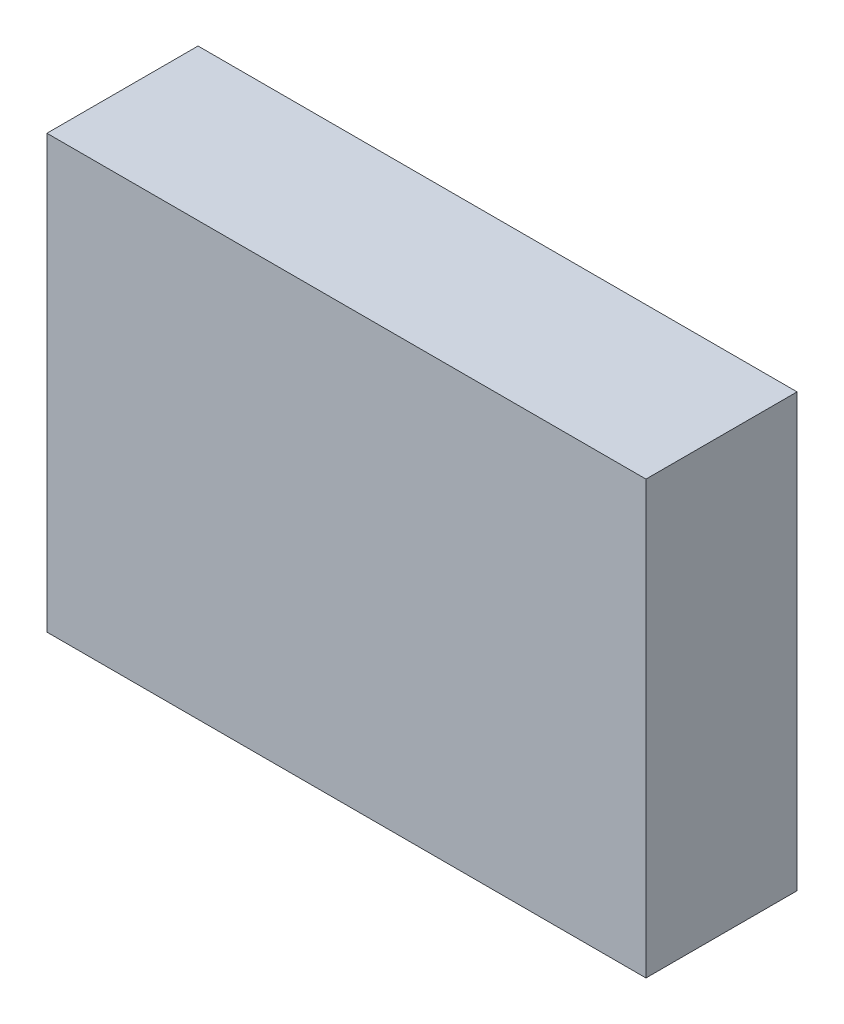
SolidWorks part; units mm, degrees
ref_plane "Front" through (0, 0, 0) normal (0, 0, 1) x (1, 0, 0)
ref_plane "Top" through (0, 0, 0) normal (0, 1, 0) x (1, 0, 0)
ref_plane "Right" through (0, 0, 0) normal (1, 0, 0) x (0, 0, -1)
sketch "Esboço1" plane through (0, 0, 0) normal (0, 0, 1) x (1, 0, 0)
  line L1 (-19.8223, 14.2975) -> (19.8223, 14.2975)
  line L2 (-19.8223, 14.2975) -> (-19.8223, -14.2975)
  line L3 (-19.8223, -14.2975) -> (19.8223, -14.2975)
  line L4 (19.8223, 14.2975) -> (19.8223, -14.2975)
  line L5 (-19.8223, 14.2975) -> (19.8223, -14.2975) construction
  line L6 (-19.8223, -14.2975) -> (19.8223, 14.2975) construction
  point P0 (0, 0)
extrude "Ressalto-extrusão1" add sketch "Esboço1" along normal mid plane 10
